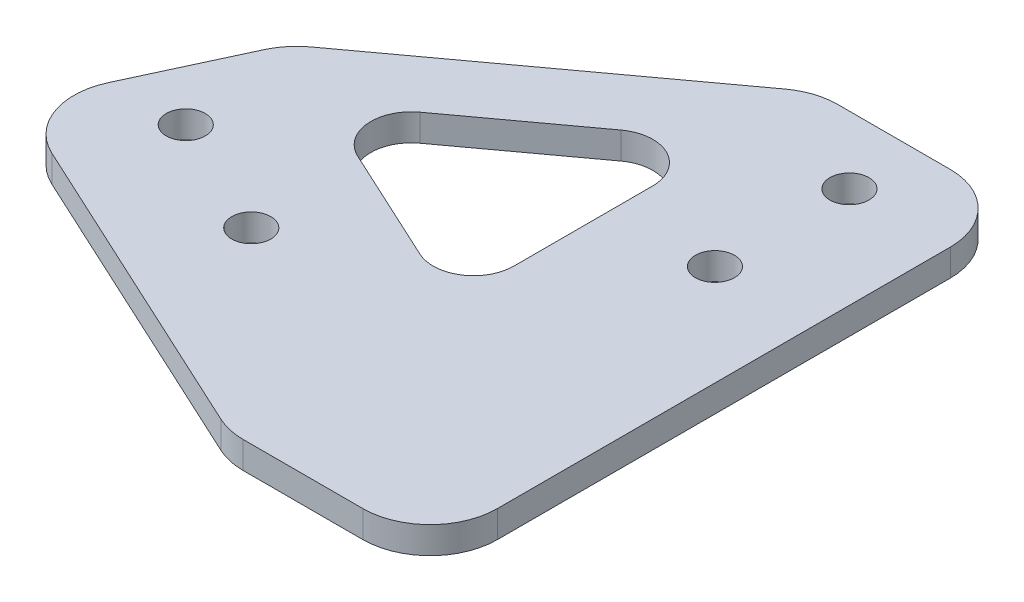
SolidWorks part; units mm, degrees
material "Thornel Mat VMA"
ref_plane "前视基准面" through (0, 0, 0) normal (0, 0, 1) x (1, 0, 0)
ref_plane "上视基准面" through (0, 0, 0) normal (0, 1, 0) x (1, 0, 0)
ref_plane "右视基准面" through (0, 0, 0) normal (1, 0, 0) x (0, 0, -1)
other "Configuration Table"
sketch "草图1" plane through (0, 0, 0) normal (0, 1, 0) x (1, 0, 0)
  line L0 (-223.6957, 111.8771) -> (230, -98.2662) construction
  line L1 (-223.6957, 111.8771) -> (-230, 98.2662) construction
  line L2 (230, -98.2662) -> (223.6957, -111.8771) construction
  line L3 (-230, 98.2662) -> (223.6957, -111.8771) construction
  line L4 (-223.6957, 111.8771) -> (223.6957, -111.8771) construction
  line L5 (230, -98.2662) -> (-230, 98.2662) construction
  line L6 (-230, 98.2662) -> (-230, 57.8051) construction
  line L7 (230, -98.2662) -> (230, 90.5698) construction
  line L8 (-224.5072, 103.9875) -> (265.5077, -122.9782) construction
  line L9 (-230, 126.8771) -> (245, 126.8771) construction
  line L10 (-230, 126.8771) -> (-230, 111.8771) construction
  line L11 (-230, 111.8771) -> (245, 111.8771) construction
  line L12 (245, 126.8771) -> (245, 111.8771) construction
  line L13 (230, 126.8771) -> (245, 126.8771) construction
  line L14 (230, 126.8771) -> (230, -154.4454) construction
  line L15 (230, -154.4454) -> (245, -154.4454) construction
  line L16 (245, 126.8771) -> (245, -154.4454) construction
  line L17 (-245.2365, 119.3771) -> (263.7187, 119.3771) construction
  line L18 (-230, 126.8771) -> (-230, 98.2662) construction
  line L19 (-230, 98.2662) -> (-206.3043, 87.2908) construction
  line L20 (-206.3043, 87.2908) -> (-200, 100.9017) construction
  line L21 (-230, 126.8771) -> (-200, 126.8771) construction
  line L22 (-200, 126.8771) -> (-200, 100.9017) construction
  line L23 (237.5, -168.9709) -> (237.5, 133.9387) construction
  line L24 (207.3152, -87.7591) -> (201.0109, -101.3699)
  line L25 (201.0109, -101.3699) -> (230, -114.7971)
  line L27 (245, -111.6236) -> (245, -71.1229)
  line L28 (245, -71.1229) -> (230, -71.1229)
  line L29 (230, -71.1229) -> (207.3152, -87.7591)
  line L30 (230, -114.7971) -> (245, -114.7971)
  line L31 (245, -114.7971) -> (245, -111.6236)
  line L32 (230, -77.3234) -> (230, -98.2662)
  line L33 (230, -98.2662) -> (212.4972, -90.1592)
  line L34 (212.4972, -90.1592) -> (230, -77.3234)
  circle A0 centre (-217.7739, 100.8688) radius 1.45 construction
  circle A1 centre (-208.7, 96.6659) radius 1.45 construction
  circle A2 centre (-220, 119.3771) radius 1.45 construction
  circle A3 centre (-210, 119.3771) radius 1.45 construction
  circle A4 centre (217.7739, -100.8688) radius 1.45
  circle A5 centre (208.7, -96.6659) radius 1.45
  circle A6 centre (237.5, -86.1229) radius 1.45
  circle A7 centre (237.5, -76.1229) radius 1.45
  point P1 (0, 0)
  point P51 (211.1158, -87.7591)
  point P52 (227.6348, -75.1897)
  point P53 (228.2967, -94.1835)
  dimension "D6" = 10
  dimension "D7" = 2.9
  dimension "D10" = 10
  dimension "D12" = 10
  dimension "D14" = 2.9
  dimension "D15" = 10
  dimension "D16" = 10
  dimension "D18" = 10
  dimension "D19" = 188
  dimension "D1" = 15
  dimension "D2" = 460
  dimension "D3" = 15
  dimension "D4" = 15
  dimension "D5" = 10
  dimension "D8" = 7.5
  dimension "D9" = 10
  dimension "D11" = 500
  dimension "D13" = 7.5
  dimension "D17" = 5
  dimension "D20" = 5
  dimension "D21" = 5
extrude "凸台-拉伸1" add sketch "草图1" along normal blind 2
fillet "圆角1" radius 5 6 edges at (201.0109, 1, 101.3699) (207.3152, 1, 87.7591) (245, 1, 71.1229) (230, 1, 71.1229) (230, 1, 114.7971) (245, 1, 114.7971)
fillet "圆角2" radius 3 3 edges at (230, 1, 98.2662) (212.4972, 1, 90.1592) (230, 1, 77.3234)
